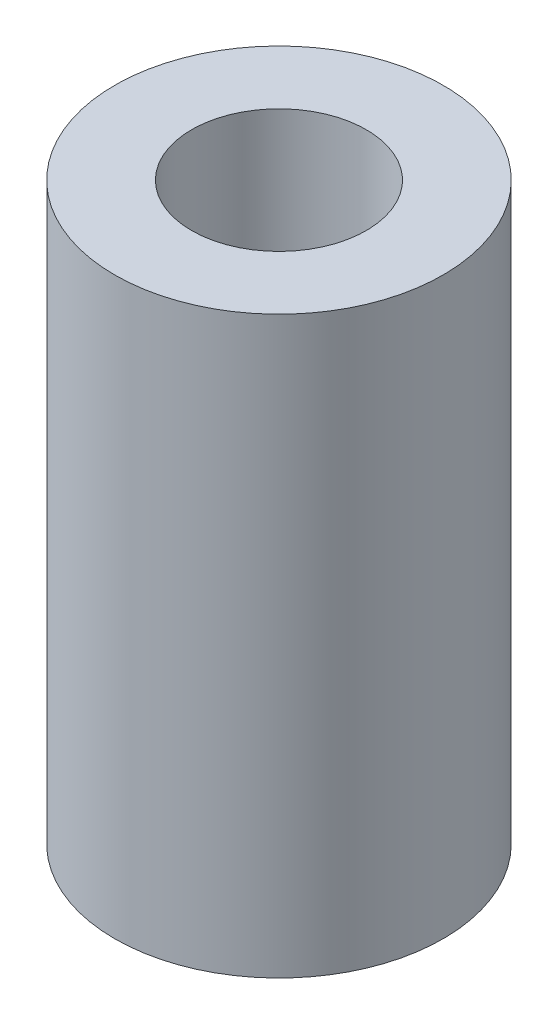
SolidWorks part; units mm, degrees
material "Chrome Stainless Steel"
ref_plane "Front" through (0, 0, 0) normal (0, 0, 1) x (1, 0, 0)
ref_plane "Top" through (0, 0, 0) normal (0, 1, 0) x (1, 0, 0)
ref_plane "Right" through (0, 0, 0) normal (1, 0, 0) x (0, 0, -1)
sketch "Sketch1" plane through (0, 0, 0) normal (0, 1, 0) x (1, 0, 0)
  circle A0 centre (0, 0) radius 6.35
  circle A1 centre (0, 0) radius 3.3782
  dimension "D1" = 6.7564
  dimension "D2" = 12.7
extrude "Extrude1" add sketch "Sketch1" along normal blind 22.225
